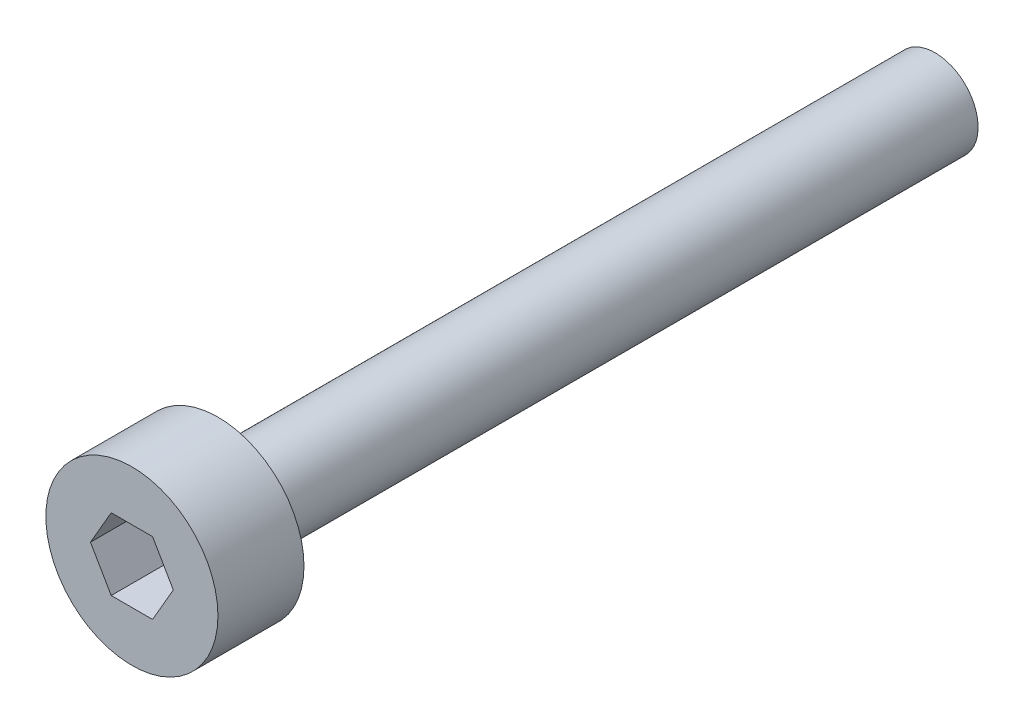
SolidWorks part; units mm, degrees
ref_plane "正面" through (0, 0, 0) normal (0, 0, 1) x (1, 0, 0)
ref_plane "平面" through (0, 0, 0) normal (0, 1, 0) x (1, 0, 0)
ref_plane "右側面" through (0, 0, 0) normal (1, 0, 0) x (0, 0, -1)
sketch "ｽｹｯﾁ5" plane through (0, 0, 0) normal (0, 0, 1) x (1, 0, 0)
  circle A0 centre (0, 0) radius 3
  dimension "D1" = 6
extrude "ﾎﾞｽ - 押し出し1" add sketch "ｽｹｯﾁ5" along normal blind 3
sketch "ｽｹｯﾁ6" plane through (0, 0, 3) normal (0, 0, 1) x (1, 0, 0)
  line L1 (1.4434, 0) -> (0.7217, 1.25)
  line L2 (0.7217, 1.25) -> (-0.7217, 1.25)
  line L3 (-0.7217, 1.25) -> (-1.4434, 0)
  line L4 (-1.4434, 0) -> (-0.7217, -1.25)
  line L5 (-0.7217, -1.25) -> (0.7217, -1.25)
  line L6 (0.7217, -1.25) -> (1.4434, 0)
  circle A0 centre (0, 0) radius 1.25 construction
  dimension "D1" = 2.5
extrude "ｶｯﾄ - 押し出し1" cut sketch "ｽｹｯﾁ6" against normal blind 2
sketch "ｽｹｯﾁ7" plane through (0, 0, 0) normal (0, 0, -1) x (-1, 0, 0)
  circle A0 centre (0, 0) radius 1.5
  dimension "D1" = 3
extrude "ﾎﾞｽ - 押し出し2" add sketch "ｽｹｯﾁ7" along normal blind 25
